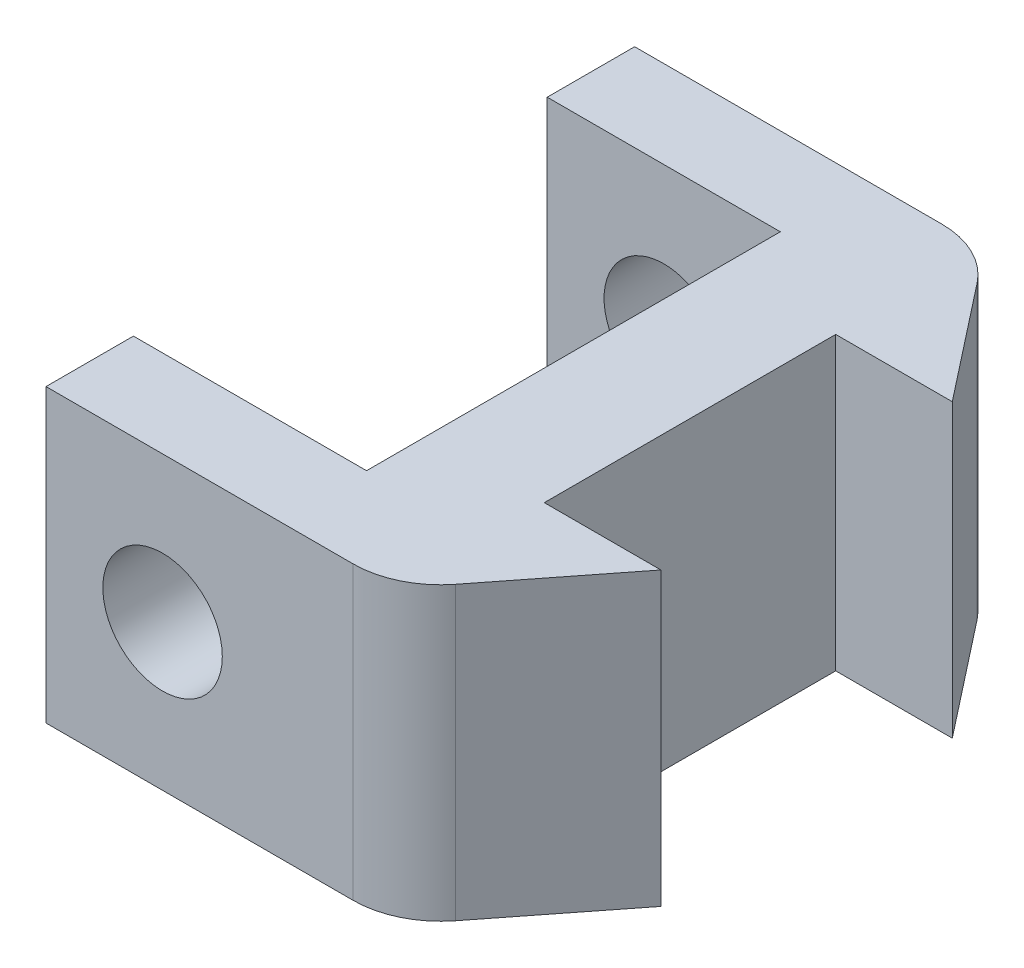
SolidWorks part; units mm, degrees
ref_plane "Front Plane" through (0, 0, 0) normal (0, 0, 1) x (1, 0, 0)
ref_plane "Top Plane" through (0, 0, 0) normal (0, 1, 0) x (1, 0, 0)
ref_plane "Right Plane" through (0, 0, 0) normal (1, 0, 0) x (0, 0, -1)
sketch "Sketch1" plane through (0, 0, 0) normal (0, 1, 0) x (1, 0, 0)
  line L1 (6, -10.1) -> (-6, -10.1)
  line L2 (6, -10.1) -> (6, 10.1)
  line L3 (6, 10.1) -> (-6, 10.1)
  line L4 (-6, -10.1) -> (-6, 10.1)
  line L5 (6, -10.1) -> (-6, 10.1) construction
  line L6 (6, 10.1) -> (-6, -10.1) construction
  line L7 (2, -7.1) -> (-6, -7.1)
  line L8 (2, -7.1) -> (2, 7.1)
  line L9 (2, 7.1) -> (-6, 7.1)
  line L10 (-6, -7.1) -> (-6, 7.1)
  line L11 (2, -7.1) -> (-6, 7.1) construction
  line L12 (2, 7.1) -> (-6, -7.1) construction
  point P0 (0, 0)
  point P6 (-2, 0)
  point P11 (0, 0)
  dimension "D1" = 14.2
  dimension "D2" = 4
  dimension "D3" = 12
  dimension "D4" = 3
extrude "Boss-Extrude1" add sketch "Sketch1" along normal blind 10 contours L9 L8 L7 L4 L1 L2 L3
sketch "Sketch2" plane through (0, 0, -7.1) normal (0, 0, 1) x (1, 0, 0)
  line L0 (2, 0) -> (-6, 10)
  circle A0 centre (-2, 5) radius 2.05
  dimension "D1" = 4.1
extrude "Cut-Extrude1" cut sketch "Sketch2" against normal through all both and the other way through all contours L0 A0 | L0 A0
sketch "Sketch3" plane through (0, 10, 0) normal (0, 1, 0) x (1, 0, 0)
  line L0 (6, 10.1) -> (10, 5)
  line L1 (10, 5) -> (10, -5)
  line L2 (10, -5) -> (6, -10.1)
  line L3 (10, -5) -> (6, -5)
  line L4 (6, -10.1) -> (6, 10.1) construction
  line L5 (10, 5) -> (6, 5)
  point P9 (10, 0)
  line M8 (6, -10.1) -> (6, 10.1)
  dimension "D1" = 10
  dimension "D2" = 4
extrude "Boss-Extrude2" add sketch "Sketch3" against normal up to surface (10 mm away) contours L5 L0 M8 | L2 L3 M8 up to face at (-1, 0, 0)
fillet "Fillet1" radius 3 2 edges at (6, 5, -10.1) (6, 5, 10.1)
